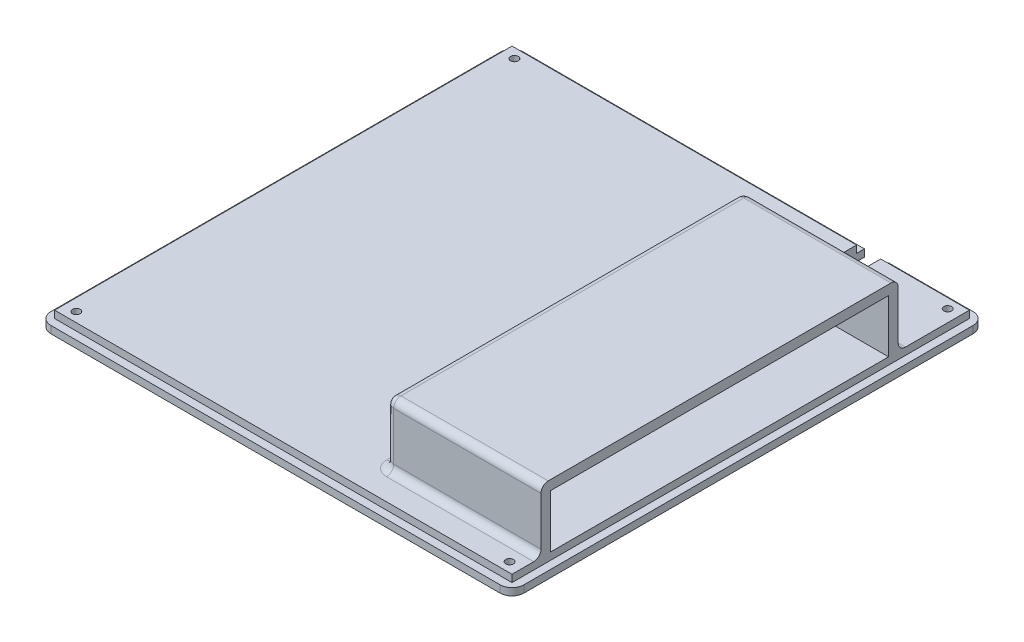
SolidWorks part; units mm, degrees
ref_plane "Front Plane" through (0, 0, 0) normal (0, 0, 1) x (1, 0, 0)
ref_plane "Top Plane" through (0, 0, 0) normal (0, 1, 0) x (1, 0, 0)
ref_plane "Right Plane" through (0, 0, 0) normal (1, 0, 0) x (0, 0, -1)
sketch "Sketch1" plane through (0, 0, 0) normal (0, 1, 0) x (1, 0, 0)
  line L1 (-98, 98) -> (98, 98)
  line L2 (-98, 98) -> (-98, -98)
  line L3 (-98, -98) -> (98, -98)
  line L4 (98, 98) -> (98, -98)
  line L5 (-98, 98) -> (98, -98) construction
  line L6 (-98, -98) -> (98, 98) construction
  point P0 (0, 0)
  dimension "D1" = 196
  dimension "D2" = 196
extrude "Boss-Extrude1" add sketch "Sketch1" along normal blind 3 contours L2 L3 L4 L1
fillet "Fillet1" radius 5 4 edges at (98, 1.5, -98) (98, 1.5, 98) (-98, 1.5, -98) (-98, 1.5, 98)
sketch "Sketch2" plane through (0, 0, 0) normal (0, -1, 0) x (1, 0, 0)
  line L1 (-94.75, -94.75) -> (94.75, -94.75)
  line L2 (-94.75, -94.75) -> (-94.75, 94.75)
  line L3 (-94.75, 94.75) -> (94.75, 94.75)
  line L4 (94.75, -94.75) -> (94.75, 94.75)
  line L5 (-94.75, -94.75) -> (94.75, 94.75) construction
  line L6 (-94.75, 94.75) -> (94.75, -94.75) construction
  point P0 (0, 0)
  dimension "D1" = 189.5
  dimension "D2" = 189.5
extrude "Boss-Extrude2" add sketch "Sketch2" against normal blind 6
sketch "Sketch3" plane through (0, 6, 0) normal (0, 1, 0) x (1, 0, 0)
  line L0 (-94.75, -94.75) -> (-94.75, 94.75) construction
  line L1 (-94.75, 94.75) -> (94.75, 94.75) construction
  circle A0 centre (-89.75, 90.75) radius 1.6
  dimension "D1" = 3.2
  dimension "D2" = 5
  dimension "D3" = 4
extrude "Cut-Extrude1" cut sketch "Sketch3" against normal through all
sketch "Sketch5" plane through (0, 0, 0) normal (0, -1, 0) x (1, 0, 0)
  circle A0 centre (-89.75, -90.75) radius 3
  dimension "D1" = 6
extrude "Cut-Extrude5" cut sketch "Sketch5" against normal blind 2
mirror "Mirror1" about plane through (0, 0, 0) normal (0, 0, 1) of "Cut-Extrude5", "Cut-Extrude1"
mirror "Mirror2" about plane through (0, 0, 0) normal (1, 0, 0) of "Mirror1", "Cut-Extrude1", "Cut-Extrude5"
sketch "Sketch6" plane through (0, 6, 0) normal (0, 1, 0) x (1, 0, 0)
  line L0 (94.75, -82.75) -> (94.75, -78.75)
  line L1 (94.75, 94.75) -> (94.75, -94.75) construction
  line L2 (94.75, -78.75) -> (34.75, -78.75)
  line L3 (34.75, -78.75) -> (34.75, 61.25)
  line L4 (34.75, 61.25) -> (94.75, 61.25)
  line L5 (94.75, 61.25) -> (94.75, 65.25)
  line L6 (94.75, 65.25) -> (30.75, 65.25)
  line L7 (30.75, 65.25) -> (30.75, -82.75)
  line L8 (30.75, -82.75) -> (94.75, -82.75)
  line L10 (94.75, -94.75) -> (-94.75, -94.75) construction
  dimension "D1" = 4
  dimension "D2" = 4
  dimension "D3" = 4
  dimension "D4" = 140
  dimension "D5" = 60
  dimension "D6" = 12
extrude "Boss-Extrude3" add sketch "Sketch6" along normal blind 22
sketch "Sketch7" plane through (0, 28, 0) normal (0, 1, 0) x (1, 0, 0)
  line L1 (30.75, -82.75) -> (94.75, -82.75)
  line L2 (30.75, -82.75) -> (30.75, 65.25)
  line L3 (30.75, 65.25) -> (94.75, 65.25)
  line L4 (94.75, -82.75) -> (94.75, 65.25)
extrude "Boss-Extrude4" add sketch "Sketch7" along normal blind 4
fillet "Fillet2" radius 3 8 edges at (62.75, 32, -65.25) (30.75, 19, -65.25) (62.75, 6, -65.25) (30.75, 32, 8.75) (62.75, 32, 82.75) (30.75, 19, 82.75) (30.75, 6, 8.75) (62.75, 6, 82.75)
sketch "Sketch8" plane through (30.75, 0, 0) normal (-1, 0, 0) x (0, 0, 1)
  line L1 (-50.25, 25) -> (-0.25, 25)
  line L2 (-50.25, 25) -> (-50.25, 10)
  line L3 (-50.25, 10) -> (-0.25, 10)
  line L4 (-0.25, 25) -> (-0.25, 10)
  line L5 (-62.25, 32) -> (79.75, 32) construction
  line L7 (-65.25, 9) -> (-65.25, 29) construction
  dimension "D1" = 15
  dimension "D2" = 7
  dimension "D3" = 50
  dimension "D4" = 15
extrude "Cut-Extrude6" cut sketch "Sketch8" against normal up to next
sketch "Sketch10" plane through (0, 0, -65.25) normal (0, 0, -1) x (-1, 0, 0)
  line L1 (-55.75, 10) -> (-35.75, 10)
  line L2 (-55.75, 10) -> (-55.75, 25)
  line L3 (-55.75, 25) -> (-35.75, 25)
  line L4 (-35.75, 10) -> (-35.75, 25)
  line L5 (-94.75, 32) -> (-33.75, 32) construction
  line L6 (-30.75, 29) -> (-30.75, 9) construction
  dimension "D1" = 7
  dimension "D2" = 5
  dimension "D3" = 15
  dimension "D4" = 20
extrude "Cut-Extrude7" cut sketch "Sketch10" against normal up to next
sketch "Sketch11" plane through (0, 0, 0) normal (0, -1, 0) x (1, 0, 0)
  line L0 (-93, -98) -> (93, -98) construction
  line L1 (58, -98) -> (48, -98)
  line L2 (58, -98) -> (58, -83)
  line L4 (48, -98) -> (48, -83)
  line L5 (98, -93) -> (98, 93) construction
  arc A0 (48, -83) -> (58, -83) centre (53, -83) cw
  dimension "D1" = 40
  dimension "D2" = 15
  dimension "D3" = 10
extrude "Cut-Extrude8" cut sketch "Sketch11" against normal through all
